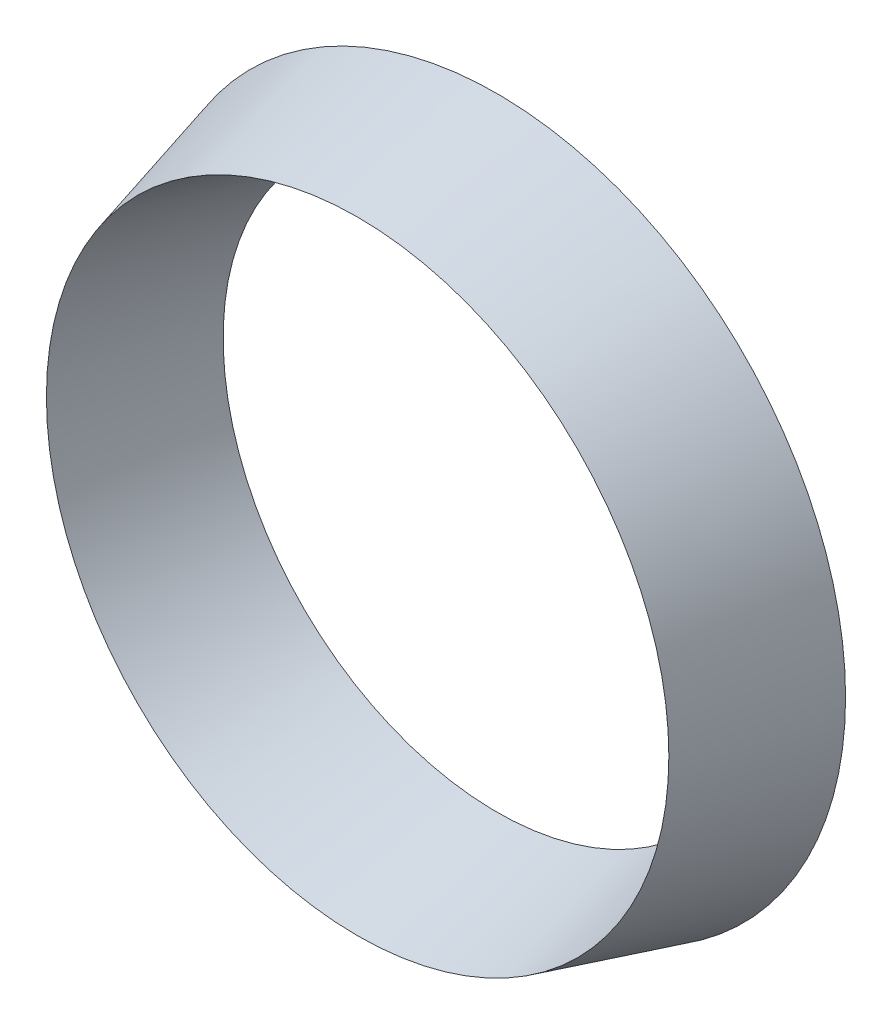
SolidWorks part; units mm, degrees
ref_plane "Plan de face" through (0, 0, 0) normal (0, 0, 1) x (1, 0, 0)
ref_plane "Plan de dessus" through (0, 0, 0) normal (0, 1, 0) x (1, 0, 0)
ref_plane "Plan de droite" through (0, 0, 0) normal (1, 0, 0) x (0, 0, -1)
sketch "Esquisse1" plane through (0, 0, 0) normal (0, 0, 1) x (1, 0, 0)
  circle A0 centre (0, 0) radius 28
  circle A1 centre (0, 0) radius 22
extrude "Boss.-Extru.1" add sketch "Esquisse1" along normal blind 70 draft 15
